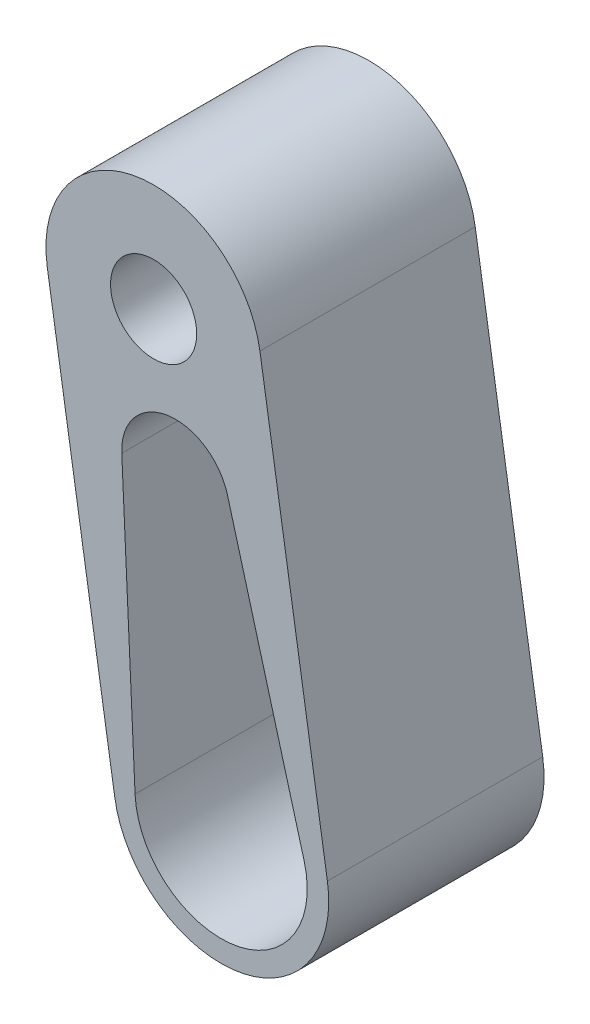
SolidWorks part; units mm, degrees
ref_plane "Front Plane" through (0, 0, 0) normal (0, 0, 1) x (1, 0, 0)
ref_plane "Top Plane" through (0, 0, 0) normal (0, 1, 0) x (1, 0, 0)
ref_plane "Right Plane" through (0, 0, 0) normal (1, 0, 0) x (0, 0, -1)
sketch "Sketch1" plane through (0, 0, 0) normal (0, 0, 1) x (1, 0, 0)
  line L42 (-64.0726, 14.9693) -> (-60.9382, -4.7836)
  line L43 (-54.1961, 16.5365) -> (-51.0618, -3.2164)
  arc A0 (-60.9382, -4.7836) -> (-51.0618, -3.2164) centre (-56, -4) ccw
  arc A1 (-54.1961, 16.5365) -> (-64.0726, 14.9693) centre (-59.1343, 15.7529) ccw
  circle A2 centre (-59.1343, 15.7529) radius 2
  circle A3 centre (-56, -4) radius 2
  dimension "D7" = 20
extrude "Boss-Extrude1" add sketch "Sketch1" along normal blind 10
sketch "Sketch2" plane through (0, 0, 10) normal (0, 0, 1) x (1, 0, 0)
  line L0 (-56, -4) -> (-59.1343, 15.7529)
  line L1 (-57.5672, 5.8764) -> (-55.3731, -7.9506)
  line L2 (-60.613, 9.2182) -> (-59.9958, -4.184)
  line L3 (-55.7054, 9.9969) -> (-52.1435, -2.9381)
  arc A0 (-59.9958, -4.184) -> (-52.1435, -2.9381) centre (-56, -4) ccw
  arc A4 (-55.7054, 9.9969) -> (-60.613, 9.2182) centre (-58.1157, 9.3332) ccw
  circle M13 centre (-56, -4) radius 2
extrude "Cut-Extrude1" cut sketch "Sketch2" against normal blind 8 contours L0 A4 L2 A0 L1 M13 | L3 A4 L0 L1 A0 M13
